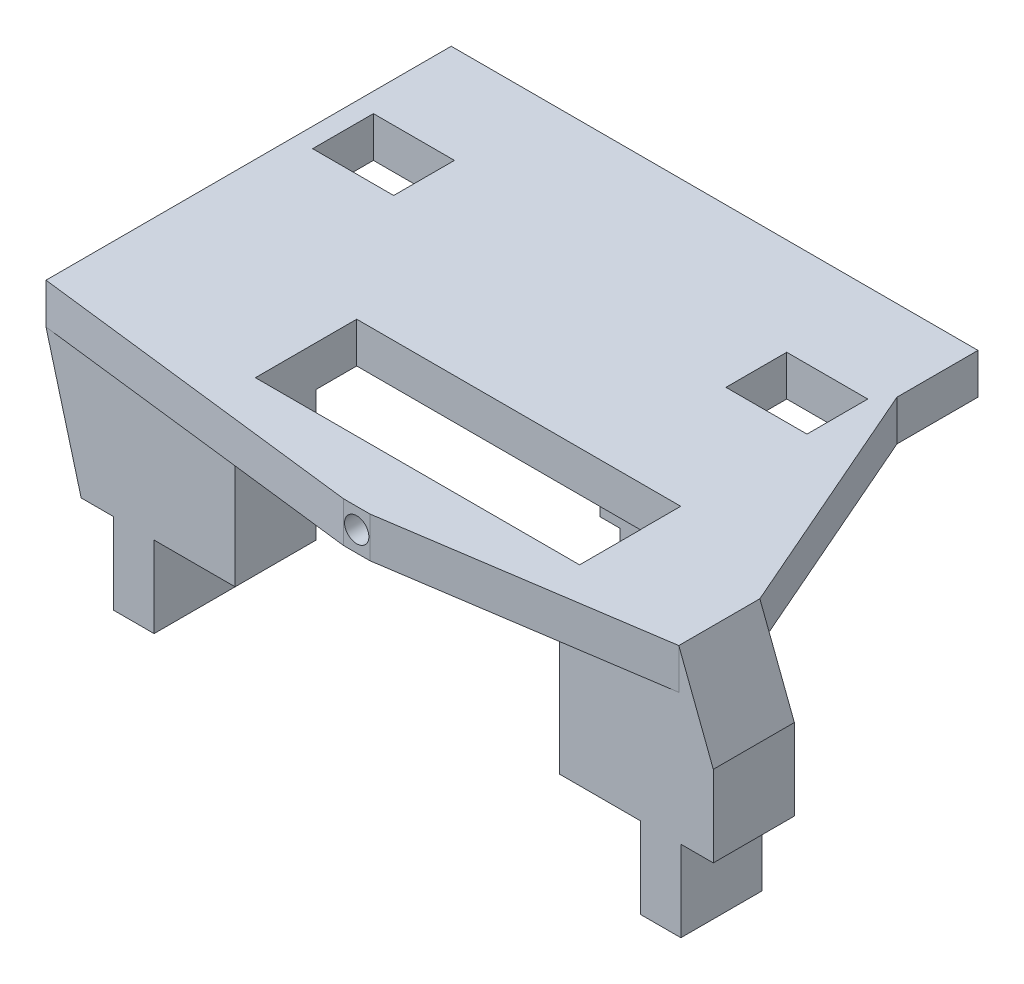
SolidWorks part; units mm, degrees
ref_plane "Alzado" through (0, 0, 0) normal (0, 0, 1) x (1, 0, 0)
ref_plane "Planta" through (0, 0, 0) normal (0, 1, 0) x (1, 0, 0)
ref_plane "Vista lateral" through (0, 0, 0) normal (1, 0, 0) x (0, 0, -1)
sketch "Croquis1" plane through (0, 0, 0) normal (0, 0, 1) x (1, 0, 0)
  line L0 (-35, 0) -> (147.6078, 0) construction
  line L1 (0, -39.1178) -> (0, 76.731) construction
  line L2 (-35, 0) -> (-30, 0)
  line L3 (-35, 0) -> (-35, 10)
  line L4 (-35, 10) -> (-39, 10)
  line L5 (-30, 0) -> (-30, 10)
  line L6 (-32.5, 0) -> (-32.5, 20) construction
  line L7 (-20, 10) -> (-30, 10)
  line L8 (-20, 10) -> (-20, 35.7237)
  line L9 (20, 10) -> (30, 10)
  line L10 (-39, 10) -> (-39, 20)
  line L11 (0, 60) -> (0, 80) construction
  line L12 (-1.5, 60) -> (-1.5, 80)
  line L13 (1.5, 60) -> (1.5, 80)
  line L14 (-39, 20) -> (-13.4477, 86.6452)
  line L15 (-20, 35.7237) -> (20, 35.7237) construction
  line L16 (20, 35.7237) -> (20, 10)
  line L17 (35, 0) -> (30, 0)
  line L18 (30, 0) -> (30, 10)
  line L19 (35, 0) -> (35, 10)
  line L20 (39, 10) -> (39, 20)
  line L23 (39, 20) -> (13.4477, 86.6452)
  line L24 (35, 10) -> (39, 10)
  arc A0 (-1.5, 60) -> (1.5, 60) centre (0, 60) ccw
  arc A1 (1.5, 80) -> (-1.5, 80) centre (0, 80) ccw
  arc A2 (14.4434, 84.0484) -> (-14.4434, 84.0484) centre (0, 80) ccw
  arc A3 (20, 35.7237) -> (-20, 35.7237) centre (0, 35.7237) ccw
  point P16 (0, 70)
  dimension "D5" = 3
  dimension "D7" = 30
  dimension "D10" = 40
  dimension "D11" = 10
  dimension "D1" = 10
  dimension "D2" = 5
  dimension "D3" = 30
  dimension "D6" = 20
  dimension "D8" = 50
  dimension "D9" = 4
extrude "Saliente-Extruir1" add sketch "Croquis1" along normal blind 10
sketch "Croquis2" plane through (0, 0, 0) normal (1, 0, 0) x (0, 0, -1)
  line L0 (0, 95) -> (-10, 95) construction
  line L2 (-2.5, 95) -> (-2.5, 50)
  line L3 (-2.5, 50) -> (-7.5, 50)
  line L4 (-7.5, 95) -> (-7.5, 50)
  line L5 (-5, 95) -> (-7.5, 50) construction
  line L6 (-2.5, 50) -> (-5, 95) construction
  line L7 (-2.5, 95) -> (-7.5, 95)
  point P0 (-5, 95)
  dimension "D1" = 5
  dimension "D2" = 45
extrude "Cortar-Extruir1" cut sketch "Croquis2" against normal mid plane 25
ref_plane "Plano1" through (0, 0, 5) normal (0, 0, -1) x (-1, 0, 0)
sketch "Croquis3" plane through (0, 0, 5) normal (0, 0, -1) x (-1, 0, 0)
  line L4 (0, 80) -> (0, 60) construction
sketch "Croquis4" plane through (0, 0, 0) normal (0, 0, -1) x (-1, 0, 0)
  line L0 (-39, 20) -> (-13.4477, 86.6452) construction
  line L1 (-36.6612, 26.1) -> (36.6612, 26.1)
  line L2 (-36.6612, 26.1) -> (-36.6612, 31.1)
  line L3 (-36.6612, 31.1) -> (36.6612, 31.1)
  line L4 (36.6612, 26.1) -> (36.6612, 31.1)
  line L5 (-35, 10) -> (-39, 10) construction
  point P6 (-37, 10)
  dimension "D1" = 16.1
  dimension "D2" = 5
extrude "Saliente-Extruir2" add sketch "Croquis4" along normal blind 30
sketch "Croquis5" plane through (-20, 0, 0) normal (1, 0, 0) x (0, 0, -1)
  line L0 (-10, 10) -> (-10, 35.7237) construction
  line L1 (-7.5, 26.1) -> (-10, 26.1)
  line L3 (-7.5, 31.1) -> (-10, 31.1)
  line L4 (-10, 26.1) -> (-10, 31.1)
  line L5 (-7.5, 31.1) -> (-7.5, 26.1)
  dimension "D1" = 5
  dimension "D2" = 2.5
  dimension "D3" = 0
extrude "Saliente-Extruir3" add sketch "Croquis5" along normal blind 50
sketch "Croquis6" plane through (-20, 0, 0) normal (1, 0, 0) x (0, 0, -1)
  line L1 (-10, 31.1) -> (45.6375, 31.1)
  line L2 (-10, 31.1) -> (-10, 95.5149)
  line L3 (-10, 95.5149) -> (45.6375, 95.5149)
  line L4 (45.6375, 31.1) -> (45.6375, 95.5149)
extrude "Cortar-Extruir2" cut sketch "Croquis6" against normal mid plane 110
sketch "Croquis7" plane through (0, 0, 10) normal (0, 0, 1) x (1, 0, 0)
  line L0 (0, 0) -> (0, 56.7642) construction
  line L1 (-36.6612, 28.6) -> (36.6612, 28.6) construction
  line L2 (-36.6612, 26.1) -> (-36.6612, 31.1) construction
  line L3 (36.6612, 31.1) -> (36.6612, 26.1) construction
  circle A0 centre (0, 28.6) radius 1.5
  dimension "D1" = 3
extrude "Cortar-Extruir3" cut sketch "Croquis7" against normal blind 5
sketch "Croquis8" plane through (0, 31.1, 0) normal (0, 1, 0) x (1, 0, 0)
  line L1 (-20, 0) -> (19.9813, 0)
  line L2 (-20, 0) -> (-20, 5)
  line L3 (-20, 5) -> (19.9813, 5)
  line L4 (19.9813, 0) -> (19.9813, 5)
  dimension "D1" = 5
extrude "Cortar-Extruir4" cut sketch "Croquis8" against normal blind 10
sketch "Croquis9" plane through (0, 31.1, 0) normal (0, 1, 0) x (1, 0, 0)
  line L2 (-36.6612, 30) -> (36.6612, 30) construction
  line L7 (10.0612, 20.5) -> (20.0612, 20.5)
  line L8 (10.0612, 20.5) -> (10.0612, 28)
  line L9 (10.0612, 28) -> (20.0612, 28)
  line L10 (20.0612, 20.5) -> (20.0612, 28)
  line L11 (36.6612, 30) -> (36.6612, 0) construction
  line L12 (-10.4396, 43.5) -> (-10.4396, -22.5745) construction
  line L13 (10.0604, 43.5) -> (-30.9396, 43.5) construction
  line L14 (-40.9403, 20.5) -> (-40.9403, 28)
  line L15 (-30.9403, 28) -> (-40.9403, 28)
  line L16 (-30.9403, 20.5) -> (-30.9403, 28)
  line L17 (-30.9403, 20.5) -> (-40.9403, 20.5)
  dimension "D1" = 9.5
  dimension "D2" = 26.6
  dimension "D3" = 7.5
  dimension "D4" = 10
extrude "Saliente-Extruir4" add sketch "Croquis9" along normal blind 21
sketch "Croquis11" plane through (0, 0, -20.5) normal (0, 0, 1) x (1, 0, 0)
  circle A2 centre (13.5604, 46.6) radius 2
  circle A3 centre (13.5604, 35.6) radius 2
  circle A6 centre (-34.4396, 46.6) radius 2
  circle A7 centre (-34.4396, 35.6) radius 2
  dimension "D1" = 4
  dimension "D2" = 4
extrude "Cortar-Extruir5" cut sketch "Croquis11" against normal blind 21
sketch "Croquis12" plane through (0, 0, -30) normal (0, 0, -1) x (-1, 0, 0)
  line L0 (22.3301, 31.1) -> (22.3301, 26.1)
  line L1 (22.3301, 26.1) -> (43.3388, 26.1)
  line L3 (22.3301, 31.1) -> (43.3388, 31.1)
  line L4 (43.3388, 26.1) -> (43.3388, 31.1)
extrude "Saliente-Extruir5" add sketch "Croquis12" against normal up to vertex (27.5 mm away)
sketch "Croquis13" plane through (0, 31.1, 0) normal (0, 1, 0) x (1, 0, 0)
  line L0 (34.7442, 0) -> (36.6612, 0)
  line L1 (-43.3388, 30) -> (36.6612, 30) construction
  line L2 (21.6612, 30) -> (36.6612, 30)
  line L3 (36.6612, 30) -> (36.6612, 0)
  line L4 (34.7442, 0) -> (21.6612, 30)
  dimension "D1" = 15
extrude "Cortar-Extruir6" cut sketch "Croquis13" against normal through all
sketch "Croquis15" plane through (0, 31.1, 0) normal (0, 1, 0) x (1, 0, 0)
  line L0 (0, 0) -> (0, 50) construction
  line L2 (-2.5, 20) -> (2.5, 20)
  line L3 (-2.5, 20) -> (-2.5, 30)
  line L4 (-2.5, 30) -> (2.5, 30)
  line L5 (2.5, 20) -> (2.5, 30)
  line L6 (-2.5, 20) -> (2.5, 30) construction
  line L7 (-2.5, 30) -> (2.5, 20) construction
  point P3 (0, 25)
  dimension "D1" = 20
  dimension "D2" = 5
  dimension "D3" = 10
extrude "Saliente-Extruir6" add sketch "Croquis15" against normal blind 31.1
ref_plane "Plano2" through (2.5, 26.1, -20) normal (0, 0, -1) x (-1, 0, 0)
sketch "Croquis18" plane through (0, 0, 10) normal (0, 0, 1) x (1, 0, 0)
  line L0 (-39, 10) -> (-43.3388, 26.1)
  line L1 (-43.3388, 26.1) -> (-36.6612, 26.1)
  line L2 (-36.6612, 26.1) -> (-39, 10)
extrude "Saliente-Extruir7" add sketch "Croquis18" against normal blind 10
ref_plane "Plano3" through (-43.3388, 31.1, 10) normal (-1, 0, 0) x (0, 0, 1)
sketch "Croquis20" plane through (0, 31.1, 0) normal (0, 1, 0) x (1, 0, 0)
  line L0 (0, -10) -> (0, -15) construction
  line L1 (34.7442, -10) -> (-43.3388, -10) construction
  line L4 (-1.6247, -15) -> (1.6247, -15)
  line L6 (0, -10) -> (1.6247, -15) construction
  line L7 (-1.6247, -15) -> (0, -10) construction
  line L8 (-43.3388, -10) -> (-1.6247, -15)
  line L9 (1.6247, -15) -> (34.7442, -10)
  line L10 (34.7442, -10) -> (-43.3388, -10)
  point P3 (0, -10)
extrude "Saliente-Extruir8" add sketch "Croquis20" against normal blind 5 separate body
sketch "Croquis21" plane through (0, 0, 7.5) normal (0, 0, -1) x (-1, 0, 0)
  circle A0 centre (0, 28.6) radius 1.5 construction
  circle A1 centre (0, 28.6) radius 1.5
extrude "Cortar-Extruir7" cut sketch "Croquis21" against normal blind 13
sketch "Croquis22" plane through (0, 52.1, 0) normal (0, 1, 0) x (1, 0, 0)
  line L0 (-40.9403, 20.5) -> (-30.9403, 20.5) construction
  line L1 (-30.9403, 20.5) -> (-30.9403, 28) construction
  line L2 (-30.9403, 28) -> (-40.9403, 28) construction
  line L3 (-40.9403, 28) -> (-40.9403, 20.5) construction
  line L4 (10.0612, 28) -> (10.0612, 20.5) construction
  line L5 (10.0612, 20.5) -> (20.0612, 20.5) construction
  line L6 (20.0612, 20.5) -> (20.0612, 28) construction
  line L7 (20.0612, 28) -> (10.0612, 28) construction
  line L8 (-40.9403, 20.5) -> (-30.9403, 20.5)
  line L9 (-30.9403, 20.5) -> (-30.9403, 28)
  line L10 (-30.9403, 28) -> (-40.9403, 28)
  line L11 (-40.9403, 28) -> (-40.9403, 20.5)
  line L12 (10.0612, 28) -> (10.0612, 20.5)
  line L13 (10.0612, 20.5) -> (20.0612, 20.5)
  line L14 (20.0612, 20.5) -> (20.0612, 28)
  line L15 (20.0612, 28) -> (10.0612, 28)
extrude "Cortar-Extruir14" cut sketch "Croquis22" against normal through all
sketch "Croquis26" plane through (0, 0, -30) normal (0, 0, -1) x (-1, 0, 0)
  line L1 (-21.6612, 31.1) -> (43.3388, 31.1)
  line L2 (-21.6612, 31.1) -> (-21.6612, 26.1)
  line L3 (-21.6612, 26.1) -> (43.3388, 26.1)
  line L4 (43.3388, 31.1) -> (43.3388, 26.1)
extrude "Saliente-Extruir11" add sketch "Croquis26" along normal blind 10
sketch "Croquis27" plane through (0, 31.1, 0) normal (0, 1, 0) x (1, 0, 0)
  line L0 (-43.3388, -10) -> (-43.3388, -8.61)
  line L1 (-43.3388, -10) -> (-43.3388, 40) construction
  line L2 (-43.3388, -8.61) -> (34.7442, -8.61)
  line L3 (34.7442, 0) -> (34.7442, -10) construction
  line L4 (1.6247, -15) -> (34.7442, -10)
  line L5 (34.7442, -10) -> (-43.3388, -10)
  line L6 (-43.3388, -10) -> (-1.6247, -15)
  line L7 (-1.6247, -15) -> (1.6247, -15)
  line L8 (1.6247, -15) -> (34.7442, -10)
  line L10 (-43.3388, -10) -> (-1.6247, -15)
  line L11 (-1.6247, -15) -> (1.6247, -15)
  line L12 (34.7442, -8.61) -> (34.7442, -10)
  dimension "D1" = 0
extrude "Saliente-Extruir12" add sketch "Croquis27" against normal blind 5
sketch "Croquis28" plane through (0, 0, 8.61) normal (0, 0, -1) x (-1, 0, 0)
  circle A0 centre (0, 28.6) radius 1.5 construction
  circle A1 centre (0, 28.6) radius 1.5
extrude "Cortar-Extruir15" cut sketch "Croquis28" against normal blind 10
ref_plane "Plano5" through (0, 0, 0) normal (-1, 0, 0) x (0, 0, 1)
sketch "Croquis29" plane through (0, 0, 0) normal (-1, 0, 0) x (0, 0, 1)
  line L0 (10, 10) -> (-32.3459, 10) construction
  line L2 (-20, 10) -> (-30, 10)
  line L6 (-20, 26.1) -> (-30, 26.1)
  line L7 (-30, 26.1) -> (-30, 0)
  line L8 (-30, 0) -> (-20, 0)
  line L9 (-20, 0) -> (-20, 26.1)
  line L10 (-20, 26.1) -> (-30, 26.1)
  line L11 (-30, 26.1) -> (-30, 10)
  line L13 (-20, 10) -> (-20, 26.1)
  dimension "D1" = 0
extrude "Saliente-Extruir13" add sketch "Croquis29" along normal mid plane 10
